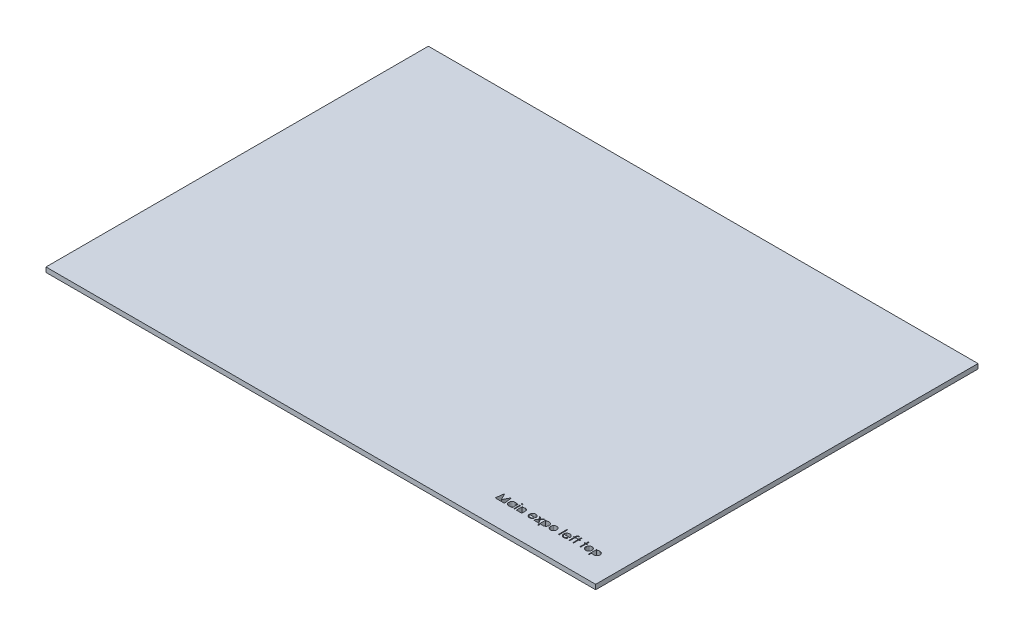
SolidWorks part; units mm, degrees
ref_plane "Front Plane" through (0, 0, 0) normal (0, 0, 1) x (1, 0, 0)
ref_plane "Top Plane" through (0, 0, 0) normal (0, 1, 0) x (1, 0, 0)
ref_plane "Right Plane" through (0, 0, 0) normal (1, 0, 0) x (0, 0, -1)
sketch "Sketch1" plane through (0, 0, 0) normal (0, 1, 0) x (1, 0, 0)
  line L0 (177.3801, -149.7149) -> (220.5219, -149.7149) construction
  line L1 (0, 0) -> (230, 0)
  line L2 (0, 0) -> (0, -160)
  line L3 (0, -160) -> (230, -160)
  line L4 (230, 0) -> (230, -160)
  line L5 (177.6493, -149.7149) -> (178.1113, -146.2149)
  line L6 (178.1113, -146.2149) -> (178.1562, -146.2149)
  line L7 (178.1562, -146.2149) -> (179.6012, -149.0867)
  line L8 (179.6012, -149.0867) -> (181.0427, -146.2149)
  line L9 (181.0427, -146.2149) -> (181.0883, -146.2149)
  line L10 (181.0883, -146.2149) -> (181.5531, -149.7149)
  line L11 (181.5531, -149.7149) -> (181.2376, -149.7149)
  line L12 (181.2376, -149.7149) -> (180.9025, -147.1964)
  line L13 (180.9025, -147.1964) -> (179.6391, -149.7149)
  line L14 (179.6391, -149.7149) -> (179.5683, -149.7149)
  line L15 (179.5683, -149.7149) -> (178.2999, -147.1908)
  line L16 (178.2999, -147.1908) -> (177.9655, -149.7149)
  line L17 (177.9655, -149.7149) -> (177.6493, -149.7149)
  line L18 (184.7839, -147.1572) -> (184.7839, -149.7149)
  line L19 (184.7839, -149.7149) -> (184.4698, -149.7149)
  line L20 (184.4698, -149.7149) -> (184.4698, -149.2725)
  line L21 (184.4698, -147.6304) -> (184.4698, -147.1572)
  line L22 (184.4698, -147.1572) -> (184.7839, -147.1572)
  line L23 (185.457, -147.1572) -> (185.7711, -147.1572)
  line L24 (185.7711, -147.1572) -> (185.7711, -149.7149)
  line L25 (185.7711, -149.7149) -> (185.457, -149.7149)
  line L26 (185.457, -149.7149) -> (185.457, -147.1572)
  line L27 (186.5339, -147.1572) -> (186.848, -147.1572)
  line L28 (186.848, -147.1572) -> (186.848, -147.6185)
  line L29 (188.7775, -148.4087) -> (188.7775, -149.7149)
  line L30 (188.7775, -149.7149) -> (188.4634, -149.7149)
  line L31 (188.4634, -149.7149) -> (188.4634, -148.5117)
  line L32 (186.848, -148.7901) -> (186.848, -149.7149)
  line L33 (186.848, -149.7149) -> (186.5339, -149.7149)
  line L34 (186.5339, -149.7149) -> (186.5339, -147.1572)
  line L35 (192.9408, -148.9072) -> (193.2198, -149.0537)
  line L36 (193.3544, -148.5033) -> (191.066, -148.5033)
  line L37 (191.0989, -148.1892) -> (193.0403, -148.1892)
  line L38 (193.7583, -147.1572) -> (194.132, -147.1572)
  line L39 (194.132, -147.1572) -> (194.7903, -148.0799)
  line L40 (194.7903, -148.0799) -> (195.4487, -147.1572)
  line L41 (195.4487, -147.1572) -> (195.8224, -147.1572)
  line L42 (195.8224, -147.1572) -> (194.9775, -148.3414)
  line L43 (194.9775, -148.3414) -> (195.957, -149.7149)
  line L44 (195.957, -149.7149) -> (195.5833, -149.7149)
  line L45 (195.5833, -149.7149) -> (194.7903, -148.6036)
  line L46 (194.7903, -148.6036) -> (193.9974, -149.7149)
  line L47 (193.9974, -149.7149) -> (193.6237, -149.7149)
  line L48 (193.6237, -149.7149) -> (194.6038, -148.3414)
  line L49 (194.6038, -148.3414) -> (193.7583, -147.1572)
  line L50 (196.316, -147.1572) -> (196.6301, -147.1572)
  line L51 (196.6301, -147.1572) -> (196.6301, -147.6304)
  line L52 (196.6301, -149.2514) -> (196.6301, -150.6572)
  line L53 (196.6301, -150.6572) -> (196.316, -150.6572)
  line L54 (196.316, -150.6572) -> (196.316, -147.1572)
  line L55 (204.1237, -146.1251) -> (204.4378, -146.1251)
  line L56 (204.4378, -146.1251) -> (204.4378, -149.7149)
  line L57 (204.4378, -149.7149) -> (204.1237, -149.7149)
  line L58 (204.1237, -149.7149) -> (204.1237, -146.1251)
  line L59 (207.2549, -148.9072) -> (207.5339, -149.0537)
  line L60 (207.6685, -148.5033) -> (205.3801, -148.5033)
  line L61 (205.413, -148.1892) -> (207.3544, -148.1892)
  line L62 (209.3737, -146.1462) -> (209.3737, -146.4729)
  line L63 (208.7924, -146.8024) -> (208.7924, -147.1572)
  line L64 (208.7924, -147.1572) -> (209.3288, -147.1572)
  line L65 (209.3288, -147.1572) -> (209.3288, -147.4713)
  line L66 (209.3288, -147.4713) -> (208.7917, -147.4713)
  line L67 (208.7917, -147.4713) -> (208.7903, -149.7149)
  line L68 (208.7903, -149.7149) -> (208.4762, -149.7149)
  line L69 (208.4762, -149.7149) -> (208.4762, -147.4713)
  line L70 (208.4762, -147.4713) -> (208.1172, -147.4713)
  line L71 (208.1172, -147.4713) -> (208.1172, -147.1572)
  line L72 (208.1172, -147.1572) -> (208.4762, -147.1572)
  line L73 (208.4762, -147.1572) -> (208.4762, -146.7484)
  line L74 (210.1365, -146.1251) -> (210.4506, -146.1251)
  line L75 (210.4506, -146.1251) -> (210.4506, -147.1572)
  line L76 (210.4506, -147.1572) -> (210.8993, -147.1572)
  line L77 (210.8993, -147.1572) -> (210.8993, -147.4713)
  line L78 (210.8993, -147.4713) -> (210.4506, -147.4713)
  line L79 (210.4506, -147.4713) -> (210.4506, -149.7149)
  line L80 (210.4506, -149.7149) -> (210.1365, -149.7149)
  line L81 (210.1365, -149.7149) -> (210.1365, -147.4713)
  line L82 (210.1365, -147.4713) -> (209.6878, -147.4713)
  line L83 (209.6878, -147.4713) -> (209.6878, -147.1572)
  line L84 (209.6878, -147.1572) -> (210.1365, -147.1572)
  line L85 (210.1365, -147.1572) -> (210.1365, -146.1251)
  line L86 (213.098, -146.1251) -> (213.4121, -146.1251)
  line L87 (213.4121, -146.1251) -> (213.4121, -147.1572)
  line L88 (213.4121, -147.1572) -> (213.8608, -147.1572)
  line L89 (213.8608, -147.1572) -> (213.8608, -147.4713)
  line L90 (213.8608, -147.4713) -> (213.4121, -147.4713)
  line L91 (213.4121, -147.4713) -> (213.4121, -149.7149)
  line L92 (213.4121, -149.7149) -> (213.098, -149.7149)
  line L93 (213.098, -149.7149) -> (213.098, -147.4713)
  line L94 (213.098, -147.4713) -> (212.6493, -147.4713)
  line L95 (212.6493, -147.4713) -> (212.6493, -147.1572)
  line L96 (212.6493, -147.1572) -> (213.098, -147.1572)
  line L97 (213.098, -147.1572) -> (213.098, -146.1251)
  line L98 (217.5852, -147.1572) -> (217.8993, -147.1572)
  line L99 (217.8993, -147.1572) -> (217.8993, -147.6304)
  line L100 (217.8993, -149.2514) -> (217.8993, -150.6572)
  line L101 (217.8993, -150.6572) -> (217.5852, -150.6572)
  line L102 (217.5852, -150.6572) -> (217.5852, -147.1572)
  spline S0 degree 3 poles (184.4698, -149.2725) (184.4026, -149.3519) (184.2941, -149.4624) (184.1274, -149.5771) (183.9988, -149.6453) (183.8638, -149.6964) (183.6738, -149.7458) (183.5254, -149.7605) (183.4251, -149.7597) knots 0 0 0 0 0.262085 0.38627 0.507165 0.6273 0.748145 1 1 1 1
  spline S1 degree 3 poles (183.4251, -149.7597) (183.3361, -149.7595) (183.2038, -149.748) (183.0338, -149.7072) (182.9125, -149.6653) (182.7968, -149.6097) (182.6858, -149.5432) (182.5799, -149.4639) (182.4808, -149.3734) (182.3896, -149.275) (182.3095, -149.17) (182.2428, -149.059) (182.187, -148.9432) (182.144, -148.8219) (182.1033, -148.6512) (182.0918, -148.5185) (182.0916, -148.429) knots 0 0 0 0 0.127433 0.189004 0.24993 0.310668 0.372329 0.434939 0.499576 0.564191 0.626735 0.688109 0.749294 0.810331 0.871901 1 1 1 1
  spline S2 degree 3 poles (182.0916, -148.429) (182.0921, -148.3412) (182.1029, -148.2106) (182.1449, -148.0428) (182.1884, -147.9235) (182.2442, -147.8092) (182.3121, -147.6997) (182.3922, -147.595) (182.4844, -147.4973) (182.5843, -147.4071) (182.6913, -147.3287) (182.8025, -147.261) (182.9197, -147.2073) (183.0413, -147.1639) (183.2125, -147.1232) (183.3455, -147.1131) (183.435, -147.1123) knots 0 0 0 0 0.126079 0.186904 0.247574 0.308003 0.369132 0.432033 0.496791 0.561611 0.624914 0.686726 0.748079 0.809582 0.871631 1 1 1 1
  spline S3 degree 3 poles (183.435, -147.1123) (183.5372, -147.1126) (183.6889, -147.1257) (183.8809, -147.1797) (184.0156, -147.2336) (184.1427, -147.3053) (184.3046, -147.4284) (184.4079, -147.5455) (184.4698, -147.6304) knots 0 0 0 0 0.254654 0.376015 0.495255 0.614798 0.738106 1 1 1 1
  spline S4 degree 3 poles (183.4392, -147.4264) (183.3487, -147.4268) (183.2133, -147.4418) (183.0423, -147.4984) (182.9213, -147.5556) (182.8087, -147.6276) (182.708, -147.7148) (182.6184, -147.8146) (182.5431, -147.9267) (182.4818, -148.0469) (182.4239, -148.214) (182.4046, -148.345) (182.4057, -148.4325) knots 0 0 0 0 0.169593 0.252476 0.336244 0.419505 0.502036 0.584775 0.669846 0.754185 0.836658 1 1 1 1
  spline S5 degree 3 poles (182.4057, -148.4325) (182.4065, -148.5194) (182.4231, -148.651) (182.483, -148.8178) (182.5442, -148.939) (182.6209, -149.0516) (182.7097, -149.1533) (182.8117, -149.2408) (182.9246, -149.3141) (183.0452, -149.3732) (183.2147, -149.4285) (183.3475, -149.4461) (183.4364, -149.4456) knots 0 0 0 0 0.162859 0.245484 0.330807 0.416493 0.499893 0.583048 0.667158 0.751312 0.833785 1 1 1 1
  spline S6 degree 3 poles (183.4364, -149.4456) (183.5267, -149.4453) (183.6623, -149.4296) (183.8351, -149.3736) (183.9589, -149.3157) (184.0742, -149.244) (184.1777, -149.16) (184.2652, -149.0623) (184.3395, -148.9549) (184.3976, -148.8372) (184.4551, -148.6678) (184.4693, -148.5323) (184.4698, -148.4416) knots 0 0 0 0 0.168664 0.252552 0.33824 0.423103 0.505556 0.586176 0.667136 0.748499 0.830452 1 1 1 1
  spline S7 degree 3 poles (184.4698, -148.4416) (184.4696, -148.3721) (184.4608, -148.269) (184.4296, -148.1369) (184.3972, -148.0434) (184.3547, -147.9548) (184.3035, -147.8703) (184.2426, -147.7905) (184.173, -147.7163) (184.0968, -147.6487) (184.0162, -147.5883) (183.9303, -147.5388) (183.8404, -147.4977) (183.7463, -147.4651) (183.6127, -147.4354) (183.5093, -147.4254) (183.4392, -147.4264) knots 0 0 0 0 0.129188 0.191219 0.251913 0.312507 0.373494 0.435152 0.498741 0.562095 0.624187 0.685476 0.746097 0.807612 0.869967 1 1 1 1
  spline S8 degree 3 poles (185.6126, -146.0803) (185.6506, -146.0803) (185.708, -146.089) (185.7758, -146.1238) (185.8203, -146.1583) (185.8585, -146.1988) (185.8945, -146.2619) (185.9059, -146.3152) (185.9057, -146.3509) knots 0 0 0 0 0.258284 0.384341 0.51198 0.638632 0.75923 1 1 1 1
  spline S9 degree 3 poles (185.9057, -146.3509) (185.9058, -146.3858) (185.8945, -146.4383) (185.8583, -146.5002) (185.8204, -146.5407) (185.7757, -146.5751) (185.708, -146.6099) (185.6506, -146.6186) (185.6126, -146.6187) knots 0 0 0 0 0.237546 0.357497 0.484917 0.613329 0.74015 1 1 1 1
  spline S10 degree 3 poles (185.6126, -146.6187) (185.5752, -146.6189) (185.5187, -146.6095) (185.4517, -146.5751) (185.407, -146.5409) (185.3698, -146.5) (185.3335, -146.4384) (185.3223, -146.3858) (185.3224, -146.3509) knots 0 0 0 0 0.256661 0.384213 0.513365 0.640443 0.761085 1 1 1 1
  spline S11 degree 3 poles (185.3224, -146.3509) (185.3222, -146.3153) (185.3335, -146.2619) (185.3696, -146.1991) (185.407, -146.158) (185.4517, -146.1238) (185.5187, -146.0894) (185.5752, -146.08) (185.6126, -146.0803) knots 0 0 0 0 0.242149 0.363437 0.489745 0.618115 0.744894 1 1 1 1
  spline S12 degree 3 poles (186.848, -147.6185) (186.9114, -147.5363) (187.0123, -147.4214) (187.1696, -147.3008) (187.2896, -147.2307) (187.4152, -147.1779) (187.5907, -147.1263) (187.7287, -147.1128) (187.8212, -147.1123) knots 0 0 0 0 0.273569 0.398988 0.51993 0.63811 0.756589 1 1 1 1
  spline S13 degree 3 poles (187.8212, -147.1123) (187.9136, -147.1129) (188.0514, -147.1279) (188.222, -147.1907) (188.3386, -147.2538) (188.4437, -147.3324) (188.5361, -147.424) (188.6124, -147.5294) (188.6636, -147.6271) (188.6974, -147.7138) (188.7186, -147.788) (188.7366, -147.8707) (188.7523, -147.9617) (188.7628, -148.0615) (188.7744, -148.2112) (188.7783, -148.328) (188.7775, -148.4087) knots 0 0 0 0 0.151178 0.223488 0.295543 0.366976 0.437131 0.507044 0.57856 0.616614 0.658756 0.704491 0.754803 0.809332 0.868274 1 1 1 1
  spline S14 degree 3 poles (188.4634, -148.5117) (188.4629, -148.4451) (188.4628, -148.3497) (188.4589, -148.2285) (188.4549, -148.1511) (188.4491, -148.0828) (188.4418, -148.0098) (188.4333, -147.9599) (188.4262, -147.9298) knots 0 0 0 0 0.34211 0.489826 0.623254 0.74008 0.841483 1 1 1 1
  spline S15 degree 3 poles (188.4262, -147.9298) (188.4087, -147.853) (188.369, -147.7434) (188.2808, -147.6218) (188.2029, -147.5496) (188.1117, -147.4935) (187.9673, -147.4393) (187.8481, -147.4259) (187.7665, -147.4264) knots 0 0 0 0 0.260833 0.378476 0.493178 0.609281 0.729981 1 1 1 1
  spline S16 degree 3 poles (187.7665, -147.4264) (187.7165, -147.4262) (187.6418, -147.4319) (187.5451, -147.4528) (187.4747, -147.4736) (187.4072, -147.5023) (187.3405, -147.5348) (187.2769, -147.5753) (187.2153, -147.6205) (187.158, -147.6706) (187.1047, -147.7235) (187.0572, -147.7797) (187.0141, -147.8385) (186.9769, -147.9007) (186.9334, -147.9874) (186.909, -148.0564) (186.8964, -148.1037) knots 0 0 0 0 0.126627 0.188984 0.25023 0.312351 0.374574 0.438148 0.50292 0.567974 0.630771 0.692935 0.754398 0.815218 0.876117 1 1 1 1
  spline S17 degree 3 poles (186.8964, -148.1037) (186.887, -148.1411) (186.8766, -148.2026) (186.8662, -148.2915) (186.8592, -148.3724) (186.8549, -148.4631) (186.8483, -148.6033) (186.8485, -148.7134) (186.848, -148.7901) knots 0 0 0 0 0.167615 0.271052 0.38946 0.520843 0.666399 1 1 1 1
  spline S18 degree 3 poles (193.2198, -149.0537) (193.1783, -149.1314) (193.1088, -149.2404) (193.0019, -149.3702) (192.9168, -149.4519) (192.8271, -149.5232) (192.7324, -149.5855) (192.6321, -149.6386) (192.5263, -149.6834) (192.414, -149.7177) (192.2516, -149.7511) (192.1247, -149.7597) (192.0384, -149.7597) knots 0 0 0 0 0.181661 0.265874 0.346355 0.4246 0.501903 0.579992 0.658443 0.738672 0.821894 1 1 1 1
  spline S19 degree 3 poles (192.0384, -149.7597) (191.9427, -149.7597) (191.8017, -149.7487) (191.6225, -149.7056) (191.4993, -149.6616) (191.3845, -149.6042) (191.278, -149.5342) (191.1792, -149.4521) (191.0912, -149.3571) (191.012, -149.2554) (190.942, -149.1495) (190.8836, -149.0395) (190.836, -148.9262) (190.7976, -148.8104) (190.7616, -148.6499) (190.7528, -148.5261) (190.7519, -148.443) knots 0 0 0 0 0.139629 0.204797 0.268135 0.329814 0.391301 0.453434 0.516552 0.579631 0.641119 0.701294 0.76081 0.819932 0.87892 1 1 1 1
  spline S20 degree 3 poles (190.7519, -148.443) (190.7528, -148.3652) (190.7601, -148.2491) (190.7917, -148.0986) (190.8239, -147.9897) (190.8654, -147.8841) (190.9336, -147.7466) (190.9988, -147.6506) (191.0463, -147.5891) knots 0 0 0 0 0.253768 0.377428 0.500551 0.623296 0.746578 1 1 1 1
  spline S21 degree 3 poles (191.0463, -147.5891) (191.1069, -147.5133) (191.2057, -147.4075) (191.3603, -147.2967) (191.4819, -147.2287) (191.6123, -147.177) (191.7988, -147.1245) (191.9467, -147.1135) (192.0461, -147.1123) knots 0 0 0 0 0.253589 0.374643 0.49534 0.616325 0.739759 1 1 1 1
  spline S22 degree 3 poles (192.0461, -147.1123) (192.149, -147.1119) (192.3009, -147.1268) (192.4935, -147.18) (192.6273, -147.2351) (192.753, -147.3063) (192.9113, -147.4254) (193.0147, -147.535) (193.0761, -147.6157) knots 0 0 0 0 0.259033 0.38188 0.502258 0.622752 0.744743 1 1 1 1
  spline S23 degree 3 poles (193.0761, -147.6157) (193.122, -147.6746) (193.1819, -147.7702) (193.2455, -147.907) (193.2839, -148.0159) (193.3149, -148.1297) (193.3455, -148.2921) (193.3528, -148.4181) (193.3544, -148.5033) knots 0 0 0 0 0.236255 0.356174 0.47725 0.60154 0.729618 1 1 1 1
  spline S24 degree 3 poles (191.066, -148.5033) (191.0678, -148.5696) (191.0766, -148.6674) (191.1069, -148.7926) (191.1382, -148.8797) (191.176, -148.9627) (191.2224, -149.0408) (191.2778, -149.1139) (191.3395, -149.1824) (191.4082, -149.2435) (191.4805, -149.2981) (191.5574, -149.3439) (191.6383, -149.3811) (191.723, -149.4102) (191.843, -149.4373) (191.9361, -149.446) (191.9992, -149.4456) knots 0 0 0 0 0.134476 0.198391 0.260753 0.321829 0.383037 0.444653 0.507398 0.569825 0.630778 0.690929 0.750945 0.811049 0.872331 1 1 1 1
  spline S25 degree 3 poles (191.9992, -149.4456) (192.0614, -149.4459) (192.1547, -149.4386) (192.2765, -149.4131) (192.3658, -149.3872) (192.4513, -149.3557) (192.5306, -149.3176) (192.6035, -149.2754) (192.6716, -149.2272) (192.7376, -149.1682) (192.8311, -149.0634) (192.8982, -148.9737) (192.9408, -148.9072) knots 0 0 0 0 0.163879 0.245659 0.327726 0.40861 0.485749 0.559169 0.630268 0.705306 0.792065 1 1 1 1
  spline S26 degree 3 poles (193.0403, -148.1892) (193.0205, -148.1085) (192.9808, -147.9946) (192.9084, -147.8577) (192.8468, -147.7721) (192.777, -147.6961) (192.6963, -147.6296) (192.6059, -147.5702) (192.5061, -147.5201) (192.4005, -147.4774) (192.2527, -147.4389) (192.1387, -147.4253) (192.0623, -147.4264) knots 0 0 0 0 0.185231 0.267501 0.3444 0.419595 0.496891 0.576638 0.660268 0.745387 0.83004 1 1 1 1
  spline S27 degree 3 poles (192.0623, -147.4264) (192.0003, -147.4263) (191.9083, -147.433) (191.79, -147.4587) (191.7053, -147.4846) (191.6246, -147.5192) (191.5196, -147.5737) (191.4487, -147.6279) (191.4032, -147.6662) knots 0 0 0 0 0.259141 0.384162 0.505992 0.629098 0.750669 1 1 1 1
  spline S28 degree 3 poles (191.4032, -147.6662) (191.3683, -147.6956) (191.3211, -147.7465) (191.2644, -147.8212) (191.225, -147.8843) (191.189, -147.9529) (191.1428, -148.0535) (191.1154, -148.1339) (191.0989, -148.1892) knots 0 0 0 0 0.22258 0.3385 0.458709 0.585535 0.717518 1 1 1 1
  spline S29 degree 3 poles (196.6301, -147.6304) (196.6922, -147.5451) (196.7967, -147.4292) (196.9579, -147.305) (197.0851, -147.2336) (197.2195, -147.1798) (197.4107, -147.1257) (197.5618, -147.1126) (197.6635, -147.1123) knots 0 0 0 0 0.263045 0.386061 0.505771 0.625178 0.746148 1 1 1 1
  spline S30 degree 3 poles (197.6635, -147.1123) (197.7532, -147.1132) (197.8864, -147.1232) (198.0579, -147.1639) (198.1794, -147.2073) (198.2967, -147.261) (198.4079, -147.3287) (198.5148, -147.4071) (198.6148, -147.4973) (198.7071, -147.5949) (198.7869, -147.7) (198.8558, -147.8089) (198.9115, -147.9235) (198.955, -148.0428) (198.997, -148.2106) (199.0078, -148.3412) (199.0083, -148.429) knots 0 0 0 0 0.128636 0.190653 0.252125 0.313446 0.375227 0.438498 0.503285 0.56801 0.630879 0.692154 0.752552 0.813191 0.873985 1 1 1 1
  spline S31 degree 3 poles (199.0083, -148.429) (199.0081, -148.5185) (198.9966, -148.6512) (198.9559, -148.8219) (198.9129, -148.9432) (198.8572, -149.0592) (198.7895, -149.1698) (198.7096, -149.275) (198.6183, -149.3733) (198.5193, -149.4639) (198.4134, -149.5432) (198.3024, -149.6097) (198.1867, -149.6653) (198.0654, -149.7072) (197.8951, -149.7481) (197.7626, -149.7594) (197.6733, -149.7597) knots 0 0 0 0 0.128034 0.189574 0.25058 0.311733 0.37325 0.435763 0.500346 0.564949 0.627528 0.689157 0.749865 0.81076 0.8723 1 1 1 1
  spline S32 degree 3 poles (197.6733, -149.7597) (197.5729, -149.7609) (197.4244, -149.7437) (197.234, -149.6912) (197.0998, -149.6346) (196.9717, -149.5623) (196.8066, -149.4428) (196.6976, -149.3316) (196.6301, -149.2514) knots 0 0 0 0 0.250548 0.37123 0.492116 0.613401 0.737997 1 1 1 1
  spline S33 degree 3 poles (197.6607, -147.4264) (197.5906, -147.4254) (197.4872, -147.4354) (197.3535, -147.4651) (197.2594, -147.4979) (197.1692, -147.5383) (197.0835, -147.5888) (197.0024, -147.6485) (196.9262, -147.7161) (196.8573, -147.7907) (196.7964, -147.8703) (196.7452, -147.9548) (196.7026, -148.0434) (196.6703, -148.1369) (196.6391, -148.269) (196.6303, -148.3721) (196.6301, -148.4416) knots 0 0 0 0 0.130024 0.192374 0.253884 0.314896 0.375806 0.438242 0.501591 0.564881 0.626533 0.687516 0.748106 0.808796 0.870822 1 1 1 1
  spline S34 degree 3 poles (196.6301, -148.4416) (196.6302, -148.5324) (196.6454, -148.6675) (196.7014, -148.8373) (196.7599, -148.9548) (196.8338, -149.0628) (196.9229, -149.1595) (197.0264, -149.2443) (197.1424, -149.3157) (197.2669, -149.3736) (197.44, -149.4293) (197.5755, -149.4455) (197.6656, -149.4456) knots 0 0 0 0 0.169344 0.251061 0.332326 0.413189 0.494299 0.576654 0.661785 0.747765 0.831967 1 1 1 1
  spline S35 degree 3 poles (197.6656, -149.4456) (197.7541, -149.4462) (197.8863, -149.4283) (198.0552, -149.3733) (198.1754, -149.3139) (198.2882, -149.2409) (198.3901, -149.1533) (198.4791, -149.0518) (198.555, -148.9388) (198.616, -148.8176) (198.6773, -148.6512) (198.6932, -148.5193) (198.6942, -148.4325) knots 0 0 0 0 0.165574 0.248159 0.332033 0.416257 0.499525 0.583039 0.668596 0.754035 0.83692 1 1 1 1
  spline S36 degree 3 poles (198.6942, -148.4325) (198.6954, -148.345) (198.6758, -148.2141) (198.6183, -148.0466) (198.5558, -147.9271) (198.4816, -147.8143) (198.3919, -147.7148) (198.2912, -147.6276) (198.1786, -147.5556) (198.0576, -147.4984) (197.8866, -147.4418) (197.7512, -147.4268) (197.6607, -147.4264) knots 0 0 0 0 0.163349 0.245826 0.330367 0.415198 0.497941 0.580476 0.66374 0.747513 0.830399 1 1 1 1
  spline S37 degree 3 poles (200.8719, -147.1123) (200.9659, -147.1113) (201.1052, -147.1249) (201.2833, -147.1695) (201.4091, -147.2147) (201.5275, -147.2755) (201.6798, -147.373) (201.7815, -147.4657) (201.8436, -147.5337) knots 0 0 0 0 0.258332 0.382134 0.503804 0.624693 0.746871 1 1 1 1
  spline S38 degree 3 poles (201.8436, -147.5337) (201.9006, -147.596) (201.977, -147.696) (202.0593, -147.8403) (202.1084, -147.9525) (202.147, -148.0689) (202.1842, -148.2319) (202.1937, -148.3581) (202.1942, -148.443) knots 0 0 0 0 0.253834 0.376506 0.498534 0.621368 0.744565 1 1 1 1
  spline S39 degree 3 poles (202.1942, -148.443) (202.1947, -148.5286) (202.183, -148.6557) (202.1443, -148.8201) (202.1036, -148.938) (202.0512, -149.0519) (201.9873, -149.1613) (201.9114, -149.2664) (201.8254, -149.3664) (201.7304, -149.4586) (201.6273, -149.5389) (201.5181, -149.6077) (201.4015, -149.6632) (201.2784, -149.7068) (201.1023, -149.7487) (200.9648, -149.7594) (200.8719, -149.7597) knots 0 0 0 0 0.123337 0.183265 0.243172 0.302898 0.363774 0.425605 0.489659 0.553785 0.616222 0.677854 0.739517 0.802097 0.865866 1 1 1 1
  spline S40 degree 3 poles (200.8719, -149.7597) (200.7785, -149.7593) (200.6404, -149.7488) (200.4639, -149.7069) (200.3407, -149.663) (200.2235, -149.6077) (200.1138, -149.5391) (200.0106, -149.4586) (199.9155, -149.3664) (199.8295, -149.2664) (199.7536, -149.1613) (199.6897, -149.0519) (199.6374, -148.938) (199.5966, -148.8201) (199.5579, -148.6557) (199.5462, -148.5286) (199.5467, -148.443) knots 0 0 0 0 0.134635 0.198324 0.260825 0.322714 0.384555 0.446913 0.510958 0.574931 0.636685 0.697483 0.757134 0.816966 0.876818 1 1 1 1
  spline S41 degree 3 poles (199.5467, -148.443) (199.5472, -148.3583) (199.5568, -148.2323) (199.5938, -148.0698) (199.6325, -147.9539) (199.682, -147.8422) (199.7632, -147.6974) (199.8409, -147.5983) (199.8973, -147.5358) knots 0 0 0 0 0.255238 0.378679 0.501088 0.622714 0.746241 1 1 1 1
  spline S42 degree 3 poles (199.8973, -147.5358) (199.9589, -147.4669) (200.0614, -147.3751) (200.2134, -147.2756) (200.3331, -147.216) (200.4588, -147.1693) (200.6377, -147.1249) (200.7773, -147.1114) (200.8719, -147.1123) knots 0 0 0 0 0.252713 0.374819 0.496436 0.617911 0.741288 1 1 1 1
  spline S43 degree 3 poles (200.8705, -147.4264) (200.8035, -147.4266) (200.7039, -147.4356) (200.576, -147.4667) (200.4845, -147.4993) (200.3969, -147.5414) (200.313, -147.5931) (200.2325, -147.6538) (200.1572, -147.7232) (200.088, -147.7991) (200.0275, -147.8799) (199.9761, -147.9644) (199.9332, -148.0527) (199.9014, -148.1456) (199.8699, -148.2758) (199.861, -148.377) (199.8608, -148.4451) knots 0 0 0 0 0.126044 0.187165 0.247399 0.30838 0.36978 0.432584 0.497641 0.562401 0.625557 0.687332 0.748313 0.809791 0.871768 1 1 1 1
  spline S44 degree 3 poles (199.8608, -148.4451) (199.8611, -148.5338) (199.8767, -148.6671) (199.935, -148.8351) (199.9935, -148.9547) (200.067, -149.0654) (200.1534, -149.1641) (200.2521, -149.2492) (200.3617, -149.3199) (200.48, -149.376) (200.6484, -149.4299) (200.7812, -149.4466) (200.8705, -149.4456) knots 0 0 0 0 0.168179 0.251488 0.335841 0.419834 0.502345 0.583649 0.665931 0.748717 0.831047 1 1 1 1
  spline S45 degree 3 poles (200.8705, -149.4456) (200.9597, -149.4465) (201.0923, -149.4302) (201.2603, -149.3759) (201.3786, -149.32) (201.4881, -149.249) (201.5875, -149.1645) (201.6732, -149.0651) (201.7466, -148.9546) (201.8061, -148.8353) (201.8641, -148.6671) (201.8799, -148.5339) (201.8801, -148.4451) knots 0 0 0 0 0.168983 0.250908 0.333708 0.416005 0.49766 0.579893 0.663902 0.748466 0.831791 1 1 1 1
  spline S46 degree 3 poles (201.8801, -148.4451) (201.8799, -148.377) (201.871, -148.2758) (201.8396, -148.1456) (201.8076, -148.0527) (201.765, -147.9642) (201.7126, -147.8802) (201.6523, -147.7988) (201.5823, -147.7235) (201.507, -147.6537) (201.4265, -147.5931) (201.3428, -147.5416) (201.2554, -147.4989) (201.1639, -147.467) (201.0364, -147.4354) (200.9372, -147.4268) (200.8705, -147.4264) knots 0 0 0 0 0.128274 0.19027 0.251768 0.312769 0.374793 0.43797 0.503047 0.568125 0.63095 0.692369 0.752973 0.813641 0.874355 1 1 1 1
  spline S47 degree 3 poles (207.5339, -149.0537) (207.4924, -149.1314) (207.4229, -149.2404) (207.316, -149.3702) (207.2309, -149.4519) (207.1412, -149.5232) (207.0465, -149.5855) (206.9462, -149.6386) (206.8404, -149.6834) (206.7281, -149.7177) (206.5657, -149.7511) (206.4388, -149.7597) (206.3525, -149.7597) knots 0 0 0 0 0.181661 0.265874 0.346355 0.4246 0.501903 0.579992 0.658443 0.738672 0.821894 1 1 1 1
  spline S48 degree 3 poles (206.3525, -149.7597) (206.2568, -149.7597) (206.1158, -149.7487) (205.9366, -149.7056) (205.8134, -149.6616) (205.6986, -149.6042) (205.5921, -149.5342) (205.4933, -149.4521) (205.4053, -149.3571) (205.3261, -149.2554) (205.2561, -149.1495) (205.1977, -149.0395) (205.1501, -148.9262) (205.1117, -148.8104) (205.0757, -148.6499) (205.0669, -148.5261) (205.066, -148.443) knots 0 0 0 0 0.139629 0.204797 0.268135 0.329814 0.391301 0.453434 0.516552 0.579631 0.641119 0.701294 0.76081 0.819932 0.87892 1 1 1 1
  spline S49 degree 3 poles (205.066, -148.443) (205.0669, -148.3652) (205.0742, -148.2491) (205.1058, -148.0986) (205.138, -147.9897) (205.1796, -147.8841) (205.2477, -147.7466) (205.3129, -147.6506) (205.3604, -147.5891) knots 0 0 0 0 0.253768 0.377428 0.500551 0.623296 0.746578 1 1 1 1
  spline S50 degree 3 poles (205.3604, -147.5891) (205.421, -147.5133) (205.5198, -147.4075) (205.6744, -147.2967) (205.796, -147.2287) (205.9264, -147.177) (206.1129, -147.1245) (206.2608, -147.1135) (206.3602, -147.1123) knots 0 0 0 0 0.253589 0.374643 0.49534 0.616325 0.739759 1 1 1 1
  spline S51 degree 3 poles (206.3602, -147.1123) (206.4631, -147.1119) (206.615, -147.1268) (206.8076, -147.18) (206.9414, -147.2351) (207.0671, -147.3063) (207.2254, -147.4254) (207.3288, -147.535) (207.3902, -147.6157) knots 0 0 0 0 0.259033 0.38188 0.502258 0.622752 0.744743 1 1 1 1
  spline S52 degree 3 poles (207.3902, -147.6157) (207.4361, -147.6746) (207.496, -147.7702) (207.5596, -147.907) (207.598, -148.0159) (207.629, -148.1297) (207.6596, -148.2921) (207.6669, -148.4181) (207.6685, -148.5033) knots 0 0 0 0 0.236255 0.356174 0.47725 0.60154 0.729618 1 1 1 1
  spline S53 degree 3 poles (205.3801, -148.5033) (205.3819, -148.5696) (205.3907, -148.6674) (205.421, -148.7926) (205.4523, -148.8797) (205.4901, -148.9627) (205.5365, -149.0408) (205.5919, -149.1139) (205.6536, -149.1824) (205.7223, -149.2435) (205.7946, -149.2981) (205.8715, -149.3439) (205.9524, -149.3811) (206.0371, -149.4102) (206.1571, -149.4373) (206.2503, -149.446) (206.3133, -149.4456) knots 0 0 0 0 0.134476 0.198391 0.260753 0.321829 0.383037 0.444653 0.507398 0.569825 0.630778 0.690929 0.750945 0.811049 0.872331 1 1 1 1
  spline S54 degree 3 poles (206.3133, -149.4456) (206.3755, -149.4459) (206.4688, -149.4386) (206.5906, -149.4131) (206.6799, -149.3872) (206.7654, -149.3557) (206.8447, -149.3176) (206.9176, -149.2754) (206.9857, -149.2272) (207.0517, -149.1682) (207.1452, -149.0634) (207.2123, -148.9737) (207.2549, -148.9072) knots 0 0 0 0 0.163879 0.245659 0.327726 0.40861 0.485749 0.559169 0.630268 0.705306 0.792065 1 1 1 1
  spline S55 degree 3 poles (207.3544, -148.1892) (207.3346, -148.1085) (207.2949, -147.9946) (207.2225, -147.8577) (207.1609, -147.7721) (207.0911, -147.6961) (207.0104, -147.6296) (206.92, -147.5702) (206.8202, -147.5201) (206.7146, -147.4774) (206.5668, -147.4389) (206.4528, -147.4253) (206.3764, -147.4264) knots 0 0 0 0 0.185231 0.267501 0.3444 0.419595 0.496891 0.576638 0.660268 0.745387 0.83004 1 1 1 1
  spline S56 degree 3 poles (206.3764, -147.4264) (206.3144, -147.4263) (206.2224, -147.433) (206.1041, -147.4587) (206.0194, -147.4846) (205.9387, -147.5192) (205.8337, -147.5737) (205.7628, -147.6279) (205.7173, -147.6662) knots 0 0 0 0 0.259141 0.384162 0.505992 0.629098 0.750669 1 1 1 1
  spline S57 degree 3 poles (205.7173, -147.6662) (205.6824, -147.6956) (205.6352, -147.7465) (205.5785, -147.8212) (205.5391, -147.8843) (205.5031, -147.9529) (205.4569, -148.0535) (205.4295, -148.1339) (205.413, -148.1892) knots 0 0 0 0 0.22258 0.3385 0.458709 0.585535 0.717518 1 1 1 1
  spline S58 degree 3 poles (209.3737, -146.4729) (209.3176, -146.4495) (209.2139, -146.4117) (209.1046, -146.3945) (209.0554, -146.3944) knots 0 0 0 0 0.553028 1 1 1 1
  spline S59 degree 3 poles (209.0554, -146.3944) (209.0252, -146.3955) (208.9807, -146.3977) (208.9264, -146.4158) (208.8915, -146.4328) (208.8626, -146.4542) (208.8378, -146.4756) (208.8198, -146.4998) (208.8101, -146.5223) (208.8041, -146.5432) (208.8023, -146.5645) (208.798, -146.5908) (208.7967, -146.6229) (208.794, -146.66) (208.7942, -146.7206) (208.791, -146.7685) (208.7924, -146.8024) knots 0 0 0 0 0.158724 0.229424 0.297719 0.360776 0.416988 0.468546 0.516675 0.544534 0.581509 0.628334 0.683433 0.749506 0.822818 1 1 1 1
  spline S60 degree 3 poles (208.4762, -146.7484) (208.4754, -146.7049) (208.4785, -146.6423) (208.4826, -146.5618) (208.4883, -146.5092) (208.495, -146.4614) (208.5045, -146.419) (208.5136, -146.3809) (208.5299, -146.3378) (208.5543, -146.289) (208.5939, -146.2373) (208.6413, -146.191) (208.6979, -146.152) (208.7616, -146.1196) (208.8588, -146.0876) (208.9375, -146.0812) (208.9908, -146.0803) knots 0 0 0 0 0.133856 0.192948 0.247916 0.296642 0.341504 0.38163 0.416905 0.483173 0.548917 0.616062 0.686302 0.759645 0.83539 1 1 1 1
  spline S61 degree 3 poles (208.9908, -146.0803) (209.0498, -146.0809) (209.1796, -146.093) (209.3055, -146.1269) (209.3737, -146.1462) knots 0 0 0 0 0.453863 1 1 1 1
  spline S62 degree 3 poles (215.6347, -147.1123) (215.7288, -147.1113) (215.868, -147.1249) (216.0461, -147.1695) (216.1719, -147.2147) (216.2903, -147.2755) (216.4427, -147.373) (216.5443, -147.4657) (216.6064, -147.5337) knots 0 0 0 0 0.258332 0.382134 0.503804 0.624693 0.746871 1 1 1 1
  spline S63 degree 3 poles (216.6064, -147.5337) (216.6635, -147.596) (216.7399, -147.696) (216.8221, -147.8403) (216.8712, -147.9525) (216.9098, -148.0689) (216.947, -148.2319) (216.9565, -148.3581) (216.957, -148.443) knots 0 0 0 0 0.253834 0.376506 0.498534 0.621368 0.744565 1 1 1 1
  spline S64 degree 3 poles (216.957, -148.443) (216.9575, -148.5286) (216.9458, -148.6557) (216.9072, -148.8201) (216.8664, -148.938) (216.814, -149.0519) (216.7501, -149.1613) (216.6742, -149.2664) (216.5882, -149.3664) (216.4932, -149.4586) (216.3901, -149.5389) (216.2809, -149.6077) (216.1643, -149.6632) (216.0412, -149.7068) (215.8652, -149.7487) (215.7276, -149.7594) (215.6347, -149.7597) knots 0 0 0 0 0.123337 0.183265 0.243172 0.302898 0.363774 0.425605 0.489659 0.553785 0.616222 0.677854 0.739517 0.802097 0.865866 1 1 1 1
  spline S65 degree 3 poles (215.6347, -149.7597) (215.5413, -149.7593) (215.4033, -149.7488) (215.2267, -149.7069) (215.1035, -149.663) (214.9864, -149.6077) (214.8766, -149.5391) (214.7734, -149.4586) (214.6783, -149.3664) (214.5923, -149.2664) (214.5164, -149.1613) (214.4525, -149.0519) (214.4002, -148.938) (214.3594, -148.8201) (214.3208, -148.6557) (214.3091, -148.5286) (214.3096, -148.443) knots 0 0 0 0 0.134635 0.198324 0.260825 0.322714 0.384555 0.446913 0.510958 0.574931 0.636685 0.697483 0.757134 0.816966 0.876818 1 1 1 1
  spline S66 degree 3 poles (214.3096, -148.443) (214.3101, -148.3583) (214.3196, -148.2323) (214.3566, -148.0698) (214.3953, -147.9539) (214.4449, -147.8422) (214.526, -147.6974) (214.6037, -147.5983) (214.6601, -147.5358) knots 0 0 0 0 0.255238 0.378679 0.501088 0.622714 0.746241 1 1 1 1
  spline S67 degree 3 poles (214.6601, -147.5358) (214.7217, -147.4669) (214.8243, -147.3751) (214.9763, -147.2756) (215.0959, -147.216) (215.2216, -147.1693) (215.4005, -147.1249) (215.5401, -147.1114) (215.6347, -147.1123) knots 0 0 0 0 0.252713 0.374819 0.496436 0.617911 0.741288 1 1 1 1
  spline S68 degree 3 poles (215.6333, -147.4264) (215.5663, -147.4266) (215.4667, -147.4356) (215.3388, -147.4667) (215.2473, -147.4993) (215.1597, -147.5414) (215.0758, -147.5931) (214.9954, -147.6538) (214.92, -147.7232) (214.8508, -147.7991) (214.7903, -147.8799) (214.7389, -147.9644) (214.696, -148.0527) (214.6642, -148.1456) (214.6327, -148.2758) (214.6238, -148.377) (214.6237, -148.4451) knots 0 0 0 0 0.126044 0.187165 0.247399 0.30838 0.36978 0.432584 0.497641 0.562401 0.625557 0.687332 0.748313 0.809791 0.871768 1 1 1 1
  spline S69 degree 3 poles (214.6237, -148.4451) (214.6239, -148.5338) (214.6395, -148.6671) (214.6978, -148.8351) (214.7564, -148.9547) (214.8298, -149.0654) (214.9163, -149.1641) (215.0149, -149.2492) (215.1245, -149.3199) (215.2429, -149.376) (215.4113, -149.4299) (215.544, -149.4466) (215.6333, -149.4456) knots 0 0 0 0 0.168179 0.251488 0.335841 0.419834 0.502345 0.583649 0.665931 0.748717 0.831047 1 1 1 1
  spline S70 degree 3 poles (215.6333, -149.4456) (215.7225, -149.4465) (215.8551, -149.4302) (216.0232, -149.3759) (216.1414, -149.32) (216.2509, -149.249) (216.3503, -149.1645) (216.436, -149.0651) (216.5094, -148.9546) (216.5689, -148.8353) (216.6269, -148.6671) (216.6427, -148.5339) (216.6429, -148.4451) knots 0 0 0 0 0.168983 0.250908 0.333708 0.416005 0.49766 0.579893 0.663902 0.748466 0.831791 1 1 1 1
  spline S71 degree 3 poles (216.6429, -148.4451) (216.6427, -148.377) (216.6338, -148.2758) (216.6024, -148.1456) (216.5705, -148.0527) (216.5278, -147.9642) (216.4754, -147.8802) (216.4151, -147.7988) (216.3451, -147.7235) (216.2698, -147.6537) (216.1894, -147.5931) (216.1056, -147.5416) (216.0182, -147.4989) (215.9267, -147.467) (215.7992, -147.4354) (215.7, -147.4268) (215.6333, -147.4264) knots 0 0 0 0 0.128274 0.19027 0.251768 0.312769 0.374793 0.43797 0.503047 0.568125 0.63095 0.692369 0.752973 0.813641 0.874355 1 1 1 1
  spline S72 degree 3 poles (217.8993, -147.6304) (217.9615, -147.5451) (218.0659, -147.4292) (218.2272, -147.305) (218.3543, -147.2336) (218.4887, -147.1798) (218.68, -147.1257) (218.831, -147.1126) (218.9328, -147.1123) knots 0 0 0 0 0.263045 0.386061 0.505771 0.625178 0.746148 1 1 1 1
  spline S73 degree 3 poles (218.9328, -147.1123) (219.0224, -147.1132) (219.1557, -147.1232) (219.3271, -147.1639) (219.4487, -147.2073) (219.5659, -147.261) (219.6772, -147.3287) (219.7841, -147.4071) (219.884, -147.4973) (219.9763, -147.5949) (220.0562, -147.7) (220.125, -147.8089) (220.1807, -147.9235) (220.2243, -148.0428) (220.2662, -148.2106) (220.277, -148.3412) (220.2775, -148.429) knots 0 0 0 0 0.128636 0.190653 0.252125 0.313446 0.375227 0.438498 0.503285 0.56801 0.630879 0.692154 0.752552 0.813191 0.873985 1 1 1 1
  spline S74 degree 3 poles (220.2775, -148.429) (220.2773, -148.5185) (220.2658, -148.6512) (220.2251, -148.8219) (220.1821, -148.9432) (220.1265, -149.0592) (220.0588, -149.1698) (219.9789, -149.275) (219.8876, -149.3733) (219.7885, -149.4639) (219.6826, -149.5432) (219.5716, -149.6097) (219.4559, -149.6653) (219.3346, -149.7072) (219.1643, -149.7481) (219.0318, -149.7594) (218.9426, -149.7597) knots 0 0 0 0 0.128034 0.189574 0.25058 0.311733 0.37325 0.435763 0.500346 0.564949 0.627528 0.689157 0.749865 0.81076 0.8723 1 1 1 1
  spline S75 degree 3 poles (218.9426, -149.7597) (218.8421, -149.7609) (218.6936, -149.7437) (218.5033, -149.6912) (218.3691, -149.6346) (218.2409, -149.5623) (218.0759, -149.4428) (217.9668, -149.3316) (217.8993, -149.2514) knots 0 0 0 0 0.250548 0.37123 0.492116 0.613401 0.737997 1 1 1 1
  spline S76 degree 3 poles (218.93, -147.4264) (218.8598, -147.4254) (218.7564, -147.4354) (218.6228, -147.4651) (218.5286, -147.4979) (218.4384, -147.5383) (218.3527, -147.5888) (218.2716, -147.6485) (218.1954, -147.7161) (218.1266, -147.7907) (218.0656, -147.8703) (218.0144, -147.9548) (217.9719, -148.0434) (217.9396, -148.1369) (217.9083, -148.269) (217.8995, -148.3721) (217.8993, -148.4416) knots 0 0 0 0 0.130024 0.192374 0.253884 0.314896 0.375806 0.438242 0.501591 0.564881 0.626533 0.687516 0.748106 0.808796 0.870822 1 1 1 1
  spline S77 degree 3 poles (217.8993, -148.4416) (217.8995, -148.5324) (217.9146, -148.6675) (217.9706, -148.8373) (218.0291, -148.9548) (218.1031, -149.0628) (218.1922, -149.1595) (218.2956, -149.2443) (218.4117, -149.3157) (218.5361, -149.3736) (218.7092, -149.4293) (218.8447, -149.4455) (218.9349, -149.4456) knots 0 0 0 0 0.169344 0.251061 0.332326 0.413189 0.494299 0.576654 0.661785 0.747765 0.831967 1 1 1 1
  spline S78 degree 3 poles (218.9349, -149.4456) (219.0233, -149.4462) (219.1555, -149.4283) (219.3244, -149.3733) (219.4446, -149.3139) (219.5574, -149.2409) (219.6593, -149.1533) (219.7483, -149.0518) (219.8242, -148.9388) (219.8853, -148.8176) (219.9465, -148.6512) (219.9624, -148.5193) (219.9634, -148.4325) knots 0 0 0 0 0.165574 0.248159 0.332033 0.416257 0.499525 0.583039 0.668596 0.754035 0.83692 1 1 1 1
  spline S79 degree 3 poles (219.9634, -148.4325) (219.9646, -148.345) (219.945, -148.2141) (219.8875, -148.0466) (219.8251, -147.9271) (219.7508, -147.8143) (219.6611, -147.7148) (219.5605, -147.6276) (219.4478, -147.5556) (219.3269, -147.4984) (219.1558, -147.4418) (219.0205, -147.4268) (218.93, -147.4264) knots 0 0 0 0 0.163349 0.245826 0.330367 0.415198 0.497941 0.580476 0.66374 0.747513 0.830399 1 1 1 1
  dimension "D1" = 230
  dimension "D2" = 160
extrude "Boss-Extrude1" add sketch "Sketch1" along normal blind 2
